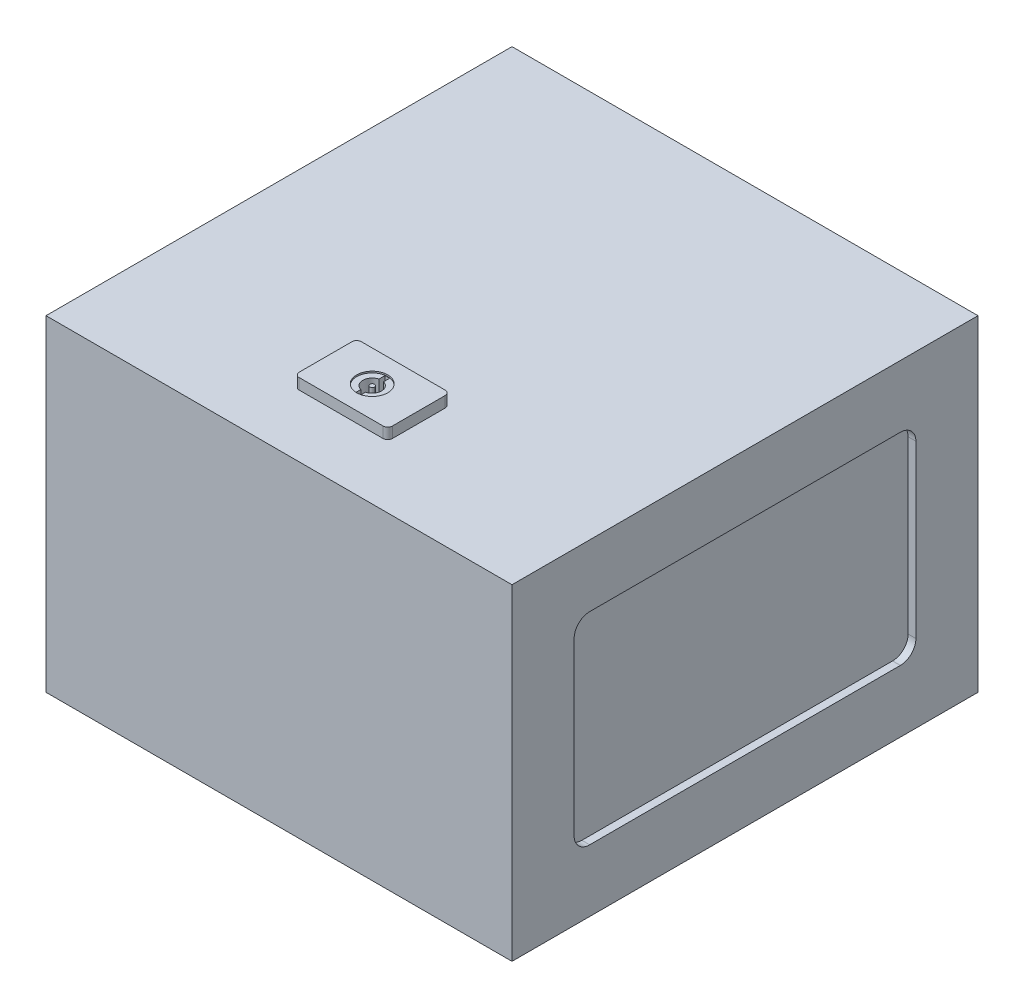
SolidWorks part; units mm, degrees
ref_plane "Front Plane" through (0, 0, 0) normal (0, 0, 1) x (1, 0, 0)
ref_plane "Top Plane" through (0, 0, 0) normal (0, 1, 0) x (1, 0, 0)
ref_plane "Right Plane" through (0, 0, 0) normal (1, 0, 0) x (0, 0, -1)
sketch "Sketch1" plane through (0, 0, 0) normal (0, 1, 0) x (1, 0, 0)
  line L1 (-150, -150) -> (150, -150)
  line L2 (-150, -150) -> (-150, 150)
  line L3 (-150, 150) -> (150, 150)
  line L4 (150, -150) -> (150, 150)
  line L5 (-150, -150) -> (150, 150) construction
  line L6 (-150, 150) -> (150, -150) construction
  point P0 (0, 0)
  dimension "D1" = 300
  dimension "D2" = 300
extrude "Boss-Extrude1" add sketch "Sketch1" along normal blind 210
sketch "Sketch2" plane through (150, 0, 0) normal (1, 0, 0) x (0, 0, -1)
  line L0 (-150, 210) -> (150, 210) construction
  line L1 (-100, 170) -> (100, 170)
  line L2 (-110, 160) -> (-110, 50)
  line L3 (-100, 40) -> (100, 40)
  line L4 (110, 160) -> (110, 50)
  line L5 (-110, 170) -> (110, 40) construction
  line L6 (-110, 40) -> (110, 170) construction
  arc A0 (-110, 50) -> (-100, 40) centre (-100, 50) ccw
  arc A1 (100, 40) -> (110, 50) centre (100, 50) ccw
  arc A2 (100, 170) -> (110, 160) centre (100, 160) cw
  arc A3 (-100, 170) -> (-110, 160) centre (-100, 160) ccw
  point P0 (0, 105)
  dimension "D3" = 10
  dimension "D1" = 105
extrude "Cut-Extrude1" cut sketch "Sketch2" against normal blind 5
sketch "Sketch3" plane through (0, 210, 0) normal (0, 1, 0) x (1, 0, 0)
  line L0 (150, -150) -> (150, 150) construction
  line L1 (-27, -110) -> (27, -110)
  line L2 (-30, -107) -> (-30, -73)
  line L3 (-27, -70) -> (27, -70)
  line L4 (30, -107) -> (30, -73)
  line L5 (-30, -110) -> (30, -70) construction
  line L6 (-30, -70) -> (30, -110) construction
  line L7 (-150, -150) -> (150, -150) construction
  arc A0 (27, -110) -> (30, -107) centre (27, -107) ccw
  arc A1 (27, -70) -> (30, -73) centre (27, -73) cw
  arc A2 (-30, -73) -> (-27, -70) centre (-27, -73) cw
  arc A3 (-27, -110) -> (-30, -107) centre (-27, -107) cw
  point P0 (0, -90)
  dimension "D2" = 3
  dimension "D3" = 150
  dimension "D4" = 40
extrude "Boss-Extrude2" add sketch "Sketch3" along normal blind 7
sketch "Sketch4" plane through (0, 217, 0) normal (0, 1, 0) x (1, 0, 0)
  line L0 (-27, -110) -> (27, -110) construction
  line L1 (-30, -73) -> (-30, -107) construction
  circle A0 centre (0, -90) radius 10
  dimension "D1" = 20
  dimension "D2" = 30
extrude "Cut-Extrude2" cut sketch "Sketch4" against normal blind 1
sketch "Sketch5" plane through (0, 216, 0) normal (0, 1, 0) x (1, 0, 0)
  line L0 (-1.5, -84.1905) -> (-1.5, -80.25)
  line L1 (-1.5, -99.75) -> (1.5, -99.75)
  line L2 (-1.5, -99.75) -> (-1.5, -95.8095)
  line L3 (-1.5, -80.25) -> (1.5, -80.25)
  line L4 (1.5, -99.75) -> (1.5, -95.8095)
  line L5 (-1.5, -99.75) -> (1.5, -80.25) construction
  line L6 (-1.5, -80.25) -> (1.5, -99.75) construction
  line L7 (1.5, -84.1905) -> (1.5, -80.25)
  arc A0 (1.5, -95.8095) -> (1.5, -84.1905) centre (0, -90) ccw
  arc A1 (-1.5, -84.1905) -> (-1.5, -95.8095) centre (0, -90) ccw
  circle A2 centre (0, -90) radius 1.5
  dimension "D1" = 19.5
  dimension "D3" = 6
  dimension "D2" = 3
extrude "Cut-Extrude3" cut sketch "Sketch5" against normal blind 10
